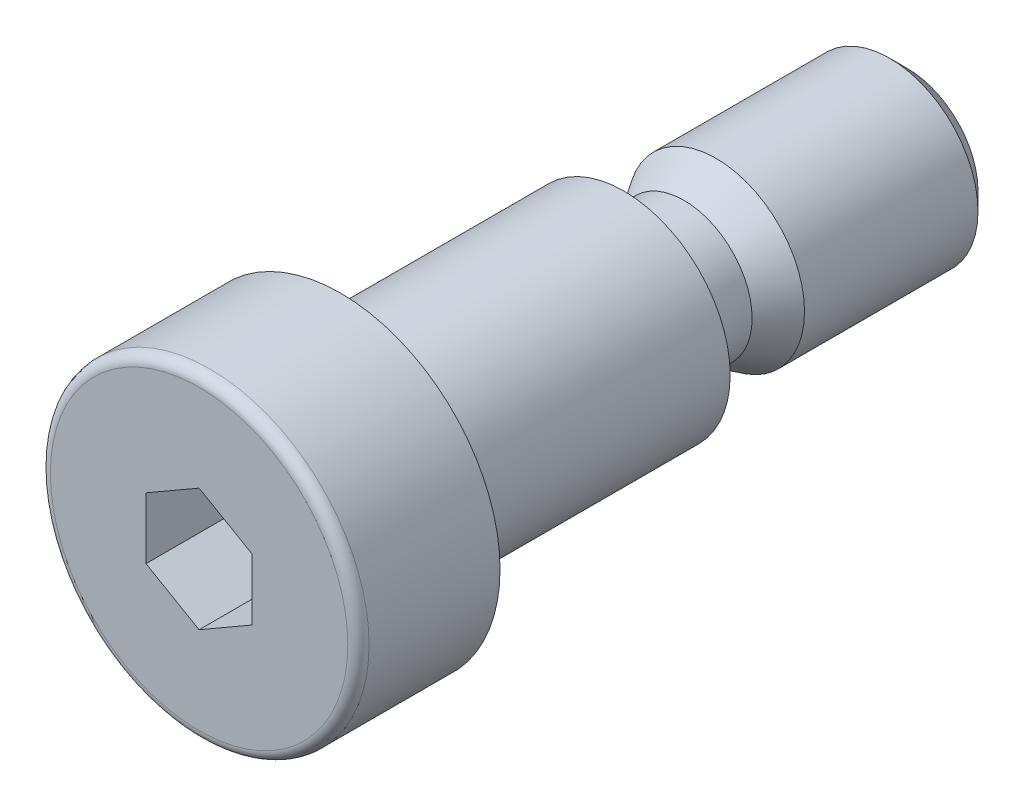
SolidWorks part; units mm, degrees
material "1.0545 (S355N)"
ref_plane "Płaszczyzna przednia" through (0, 0, 0) normal (0, 0, 1) x (1, 0, 0)
ref_plane "Płaszczyzna górna" through (0, 0, 0) normal (0, 1, 0) x (1, 0, 0)
ref_plane "Płaszczyzna prawa" through (0, 0, 0) normal (1, 0, 0) x (0, 0, -1)
sketch "Szkic1" plane through (0, 0, 0) normal (0, 1, 0) x (1, 0, 0)
  line L0 (5, 13.2) -> (3.85, 11.39)
  line L1 (9, -16) -> (-9, -16)
  line L2 (9, -16) -> (9, -8)
  line L3 (9, -8) -> (-9, -8)
  line L4 (-9, -16) -> (-9, -8)
  line L5 (6, -8) -> (-6, -8)
  line L6 (6, -8) -> (6, 8)
  line L7 (6, 8) -> (-6, 8)
  line L8 (-6, -8) -> (-6, 8)
  line L9 (-3.85, 8) -> (3.85, 8)
  line L10 (-3.85, 8) -> (-3.85, 11.39)
  line L11 (-3.85, 11.39) -> (3.85, 11.39)
  line L12 (3.85, 8) -> (3.85, 11.39)
  line L13 (5, 13.2) -> (5, 23)
  line L14 (5, 23) -> (4, 24)
  line L15 (4, 24) -> (-4, 24)
  line L16 (-4, 24) -> (-5, 23)
  line L17 (-5, 23) -> (-5, 13.2)
  line L18 (-5, 13.2) -> (-3.85, 11.39)
  line L19 (5, 13.2) -> (-5, 13.2) construction
  line L20 (5, 23) -> (-5, 23) construction
  line L21 (0, -19.9356) -> (0, 25.6583) construction
  line L22 (0, -16) -> (0, 24)
  point P4 (0, -8)
  point P14 (0, -8)
  point P15 (0, 8)
  point P16 (0, 8)
  point P17 (-6, 0)
  point P23 (0, 13.2)
  point P25 (0, 24)
  point P26 (0, 11.39)
  point P27 (0, 23)
  dimension "D1" = 18
  dimension "D2" = 8
  dimension "D3" = 12
  dimension "l1" = 16
  dimension "D5" = 7.7
  dimension "D6" = 16
  dimension "D7" = 10
  dimension "D8" = 8
  dimension "D9" = 1
  dimension "D10" = 1.81
  dimension "D11" = 9.8
revolve "Obrót1" add sketch "Szkic1" angle 360 about L22
sketch "Szkic2" plane through (0, 0, 16) normal (0, 0, 1) x (1, 0, 0)
  line L1 (3, 1.7321) -> (0, 3.4641)
  line L2 (0, 3.4641) -> (-3, 1.7321)
  line L3 (-3, 1.7321) -> (-3, -1.7321)
  line L4 (-3, -1.7321) -> (0, -3.4641)
  line L5 (0, -3.4641) -> (3, -1.7321)
  line L6 (3, -1.7321) -> (3, 1.7321)
  circle A0 centre (0, 0) radius 3 construction
  dimension "D1" = 6
extrude "Wytnij-wyciągnięcie1" cut sketch "Szkic2" against normal blind 4.9
fillet "Zaokrąglenie1" radius 0.6 1 edges at (9, 0, 16)
